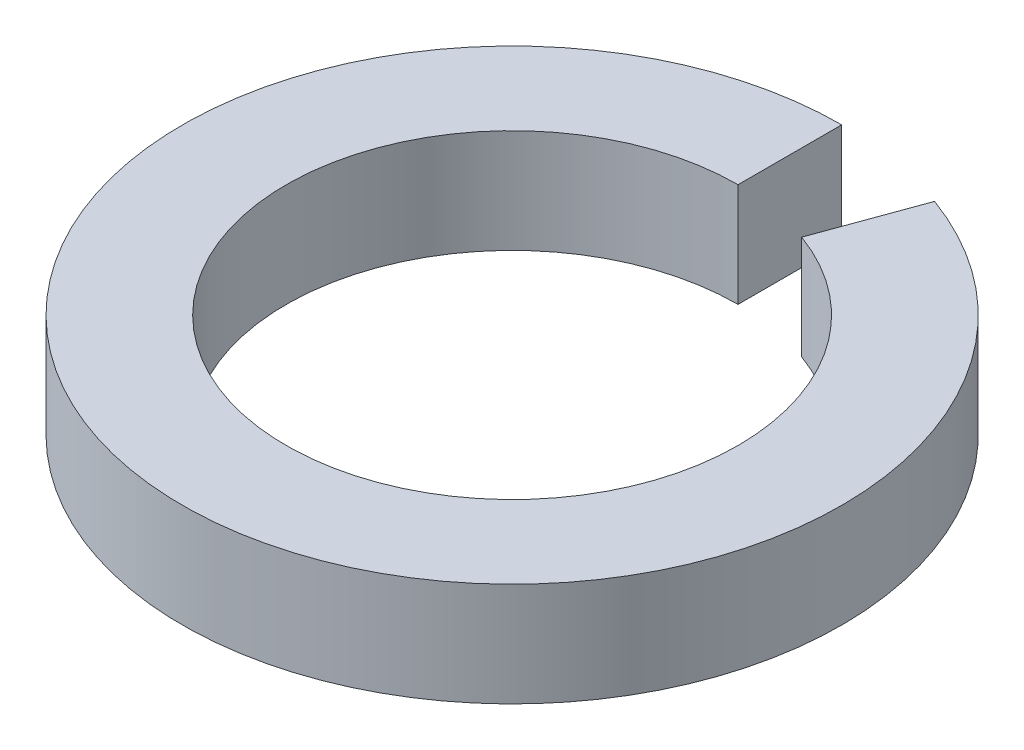
SolidWorks part; units mm, degrees
material "Plain Carbon Steel"
ref_plane "Спереди" through (0, 0, 0) normal (0, 0, 1) x (1, 0, 0)
ref_plane "Сверху" through (0, 0, 0) normal (0, 1, 0) x (1, 0, 0)
ref_plane "Справа" through (0, 0, 0) normal (1, 0, 0) x (0, 0, -1)
sketch "Sketch1" plane through (0, 0, 0) normal (0, 1, 0) x (1, 0, 0)
  line L0 (0, 3.05) -> (0, 4.45)
  line L1 (1.0432, 2.8661) -> (1.522, 4.1816)
  arc A0 (0, 3.05) -> (1.0432, 2.8661) centre (0, 0) ccw
  arc A1 (0, 4.45) -> (1.522, 4.1816) centre (0, 0) ccw
  dimension "D1" = 6.1
  dimension "D2" = 1.4
  dimension "D3" = 20
extrude "Boss-Extrude1" add sketch "Sketch1" along normal blind 1.4
